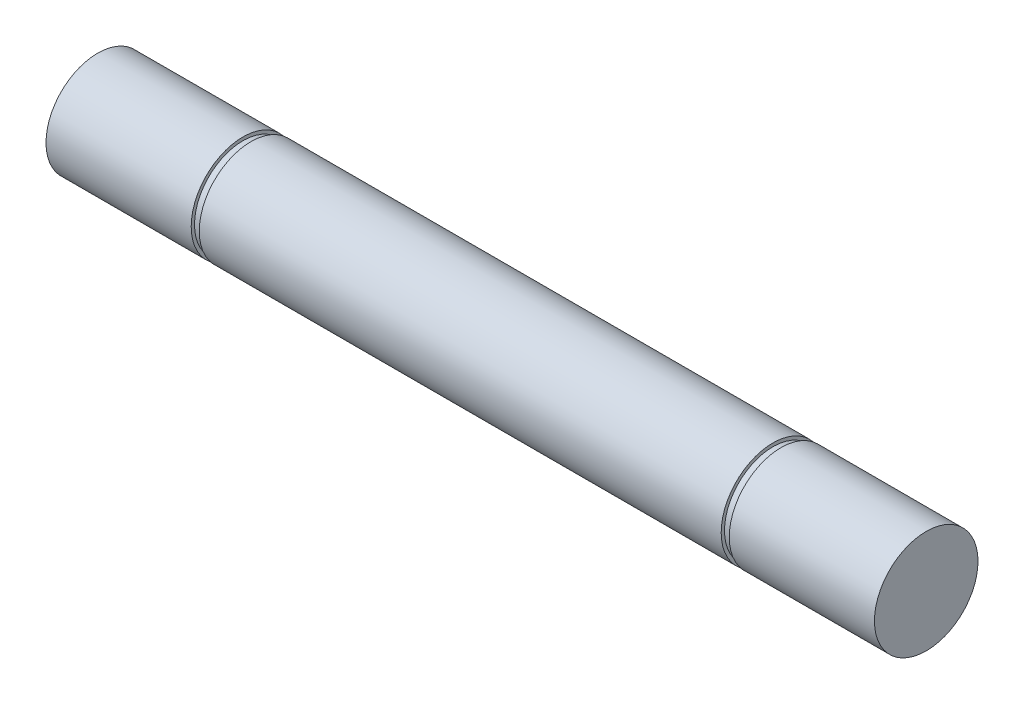
SolidWorks part; units mm, degrees
material "6061 Alloy"
ref_plane "Front Plane" through (0, 0, 0) normal (0, 0, 1) x (1, 0, 0)
ref_plane "Top Plane" through (0, 0, 0) normal (0, 1, 0) x (1, 0, 0)
ref_plane "Right Plane" through (0, 0, 0) normal (1, 0, 0) x (0, 0, -1)
sketch "Sketch1" plane through (0, 0, 0) normal (1, 0, 0) x (0, 0, -1)
  circle A0 centre (0, 0) radius 6.35
  dimension "D1" = 12.7
extrude "Boss-Extrude1" add sketch "Sketch1" along normal blind 101.6
ref_plane "Plane2" through (50.8, 0, 0) normal (-1, 0, 0) x (0, 0, 1)
ref_plane "Plane1" through (18.796, 0, 0) normal (-1, 0, 0) x (0, 0, 1)
sketch "Sketch2" plane through (18.796, 0, 0) normal (-1, 0, 0) x (0, 0, 1)
  circle A0 centre (0, 0) radius 5.9436
  circle A1 centre (0, 0) radius 6.35
  circle A2 centre (0, 0) radius 6.35 construction
  dimension "D1" = 11.8872
extrude "Cut-Extrude1" cut sketch "Sketch2" along normal blind 0.9906
mirror "Mirror1" about plane through (50.8, 0, 0) normal (-1, 0, 0) of "Cut-Extrude1"
